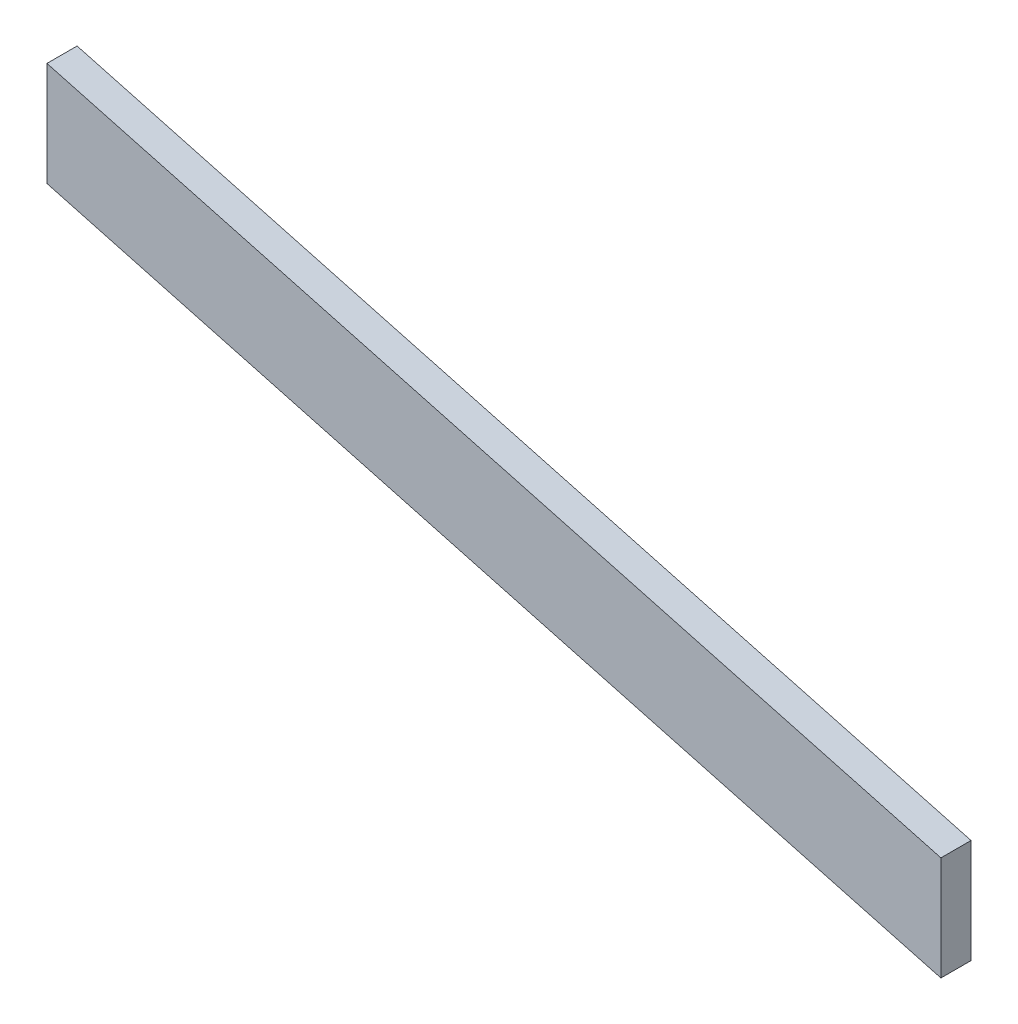
SolidWorks part; units mm, degrees
ref_plane "Front Plane" through (0, 0, 0) normal (0, 0, 1) x (1, 0, 0)
ref_plane "Top Plane" through (0, 0, 0) normal (0, 1, 0) x (1, 0, 0)
ref_plane "Right Plane" through (0, 0, 0) normal (1, 0, 0) x (0, 0, -1)
sketch "Sketch1" plane through (0, 0, 0) normal (0, 0, 1) x (1, 0, 0)
  line L0 (-108.5345, -3.9032) -> (-108.5345, 1464.0363)
  line L1 (-108.5345, -3.9032) -> (-870.5345, -3.9032)
  line L2 (-870.5345, -3.9032) -> (-870.5345, 625.8363)
  line L3 (-972.1345, 737.9573) -> (-972.1345, 834.2968)
  line L4 (-768.9345, 834.2968) -> (-768.9345, 986.6968)
  line L5 (-972.1345, 834.2968) -> (-768.9345, 834.2968)
  line L6 (-528.0858, 1843.9468) -> (-737.1845, 1843.9468)
  line L7 (-968.4148, 728.977) -> (-874.2542, 634.8165)
  line L8 (-737.1845, 1672.0154) -> (-737.1845, 1762.6932)
  line L9 (-520.195, 1875.6968) -> (-756.2345, 1875.6968)
  line L10 (-112.2542, 1473.0165) -> (-511.2148, 1871.977)
  line L11 (-737.1845, 1692.941) -> (-241.631, 1467.6894)
  line L12 (-596.8655, 1608.234) -> (-737.1845, 983.1768)
  line L13 (-763.9746, 985.3593) -> (-203.7845, 834.2968)
  line L14 (-761.4898, 1669.1128) -> (-638.6318, 1613.2683)
  line L15 (-631.4955, 1598.9249) -> (-768.9345, 986.6968)
  line L16 (-768.9345, 1680.6745) -> (-768.9345, 1862.9968)
  line L17 (-737.1845, 1780.4468) -> (-737.1845, 1843.9468)
  line L18 (-737.1845, 1692.941) -> (-737.1845, 1843.9468) construction
  line L19 (-737.1845, 1692.941) -> (-737.1845, 1762.6932) construction
  line L20 (-838.7845, -3.9032) -> (-838.7845, 834.2968)
  line L21 (-745.0674, 1675.5986) -> (-249.5139, 1450.347) construction
  line L22 (-140.2845, -3.9032) -> (-140.2845, 1456.1455)
  line L23 (-140.2845, 1456.1455) -> (-528.0858, 1843.9468)
  line L24 (-537.8111, 1581.3911) -> (-673.6845, 976.1369)
  line L25 (-768.9345, 966.9663) -> (-203.7845, 814.5663)
  line L26 (-737.1845, 1672.0154) -> (-203.7845, 1429.5608)
  line L27 (-528.0858, 1843.9468) -> (-554.3883, 1780.4468)
  line L28 (-140.2845, 1456.1455) -> (-203.7845, 1429.8429)
  line L29 (-775.2845, -3.9032) -> (-775.2845, 834.2968)
  line L30 (-773.8944, 968.3038) -> (-208.7444, 815.9038) construction
  line L31 (-203.7845, -3.9032) -> (-203.7845, 1429.8429)
  line L32 (-203.7845, 1429.8429) -> (-554.3883, 1780.4468)
  line L33 (-554.3883, 1780.4468) -> (-737.1845, 1780.4468)
  line L34 (-768.9345, 966.9663) -> (-763.9746, 985.3593)
  line L35 (-737.1845, 1762.6932) -> (-369.5099, 1595.5683)
  line L36 (-673.6845, 1733.8295) -> (-599.2171, 1699.9807) construction
  line L37 (-737.1845, 1692.941) -> (-625.4936, 1642.1724) construction
  line L38 (-538.5586, 1578.0615) -> (-673.6845, 976.1369) construction
  line L39 (-600.5166, 1591.9704) -> (-737.1845, 983.1768) construction
  line L40 (-554.3883, 1780.4468) -> (-673.6845, 1780.4468) construction
  line L41 (-203.7845, 91.3468) -> (-203.7845, 1429.8429) construction
  line L42 (-140.2845, 27.8468) -> (-140.2845, 1456.1455) construction
  line L43 (-775.2845, 91.3468) -> (-775.2845, 625.8363) construction
  line L44 (-838.7845, 27.8468) -> (-838.7845, 625.8363) construction
  line L45 (-203.7845, 91.3468) -> (-775.2845, 91.3468) construction
  line L46 (-140.2845, 27.8468) -> (-838.7845, 27.8468) construction
  line L47 (-940.3845, 745.8481) -> (-851.8036, 657.2672) construction
  line L48 (-843.7807, 739.0468) -> (-806.9023, 702.1685) construction
  line L49 (-843.7807, 739.0468) -> (-673.6845, 739.0468) construction
  line L50 (-940.3845, 802.5468) -> (-737.1845, 802.5468) construction
  line L51 (-940.3845, 745.8481) -> (-940.3845, 802.5468) construction
  line L52 (-843.7807, 739.0468) -> (-843.7807, 739.0468) construction
  line L53 (-673.6845, 1733.8295) -> (-673.6845, 1780.4468) construction
  line L54 (-756.2345, 1692.941) -> (-756.2345, 1792.2779) construction
  line L55 (-756.2345, 1792.2779) -> (-361.627, 1612.9108) construction
  line L56 (-673.6845, 739.0468) -> (-673.6845, 976.1369) construction
  line L57 (-737.1845, 802.5468) -> (-737.1845, 983.1768) construction
  line L58 (-768.9345, 986.6968) -> (-203.7845, 834.2968) construction
  line L59 (-203.7845, 834.2968) -> (-208.7444, 815.9038)
  line L60 (-768.9345, 901.198) -> (-203.7845, 748.798)
  line L61 (-846.7775, 922.1894) -> (-163.9675, 738.0608) construction
  line L62 (-768.9345, 966.9663) -> (-208.7444, 815.9038) construction
  line L64 (-808.7515, 1063.2022) -> (-125.9415, 879.0737) construction
  line L65 (-125.9415, 879.0737) -> (-163.9675, 738.0608) construction
  line L66 (-846.7775, 922.1894) -> (-808.7515, 1063.2022) construction
  arc A0 (-108.5345, 1464.0363) -> (-112.2542, 1473.0165) centre (-121.2345, 1464.0363) ccw
  arc A1 (-511.2148, 1871.977) -> (-520.195, 1875.6968) centre (-520.195, 1862.9968) ccw
  arc A2 (-768.9345, 1862.9968) -> (-756.2345, 1875.6968) centre (-756.2345, 1862.9968) cw
  arc A3 (-768.9345, 1680.6745) -> (-761.4898, 1669.1128) centre (-756.2345, 1680.6745) ccw
  arc A4 (-631.4955, 1598.9249) -> (-638.6318, 1613.2683) centre (-643.8871, 1601.7067) ccw
  arc A5 (-972.1345, 737.9573) -> (-968.4148, 728.977) centre (-959.4345, 737.9573) ccw
  arc A6 (-870.5345, 625.8363) -> (-874.2542, 634.8165) centre (-883.2345, 625.8363) ccw
  arc A7 (-737.1845, 1843.9468) -> (-737.1845, 1843.9468) centre (-737.1845, 1843.9468) cw
  arc A8 (-737.1845, 1692.941) -> (-737.1845, 1692.941) centre (-737.1845, 1692.941) ccw
  arc A12 (-140.2845, 1456.1455) -> (-140.2845, 1456.1455) centre (-140.2845, 1456.1455) ccw
  arc A13 (-528.0858, 1843.9468) -> (-528.0858, 1843.9468) centre (-528.0858, 1843.9468) ccw
  arc A14 (-600.5166, 1591.9704) -> (-625.4936, 1642.1724) centre (-643.8871, 1601.7067) ccw construction
  arc A16 (-203.7845, 1429.8429) -> (-203.7845, 1429.8429) centre (-203.7845, 1429.8429) ccw
  arc A17 (-554.3883, 1780.4468) -> (-554.3883, 1780.4468) centre (-554.3883, 1780.4468) ccw
  arc A18 (-673.6845, 1780.4468) -> (-673.6845, 1780.4468) centre (-673.6845, 1780.4468) cw
  arc A19 (-673.6845, 1733.8295) -> (-673.6845, 1733.8295) centre (-673.6845, 1733.8295) ccw
  arc A20 (-838.7845, 625.8363) -> (-851.8036, 657.2672) centre (-883.2345, 625.8363) ccw construction
  arc A21 (-775.2845, 625.8363) -> (-806.9023, 702.1685) centre (-883.2345, 625.8363) ccw construction
  arc A22 (-843.7807, 739.0468) -> (-843.7807, 739.0468) centre (-843.7807, 739.0468) ccw construction
  arc A23 (-940.3845, 745.8481) -> (-940.3845, 745.8481) centre (-940.3845, 745.8481) ccw construction
  arc A24 (-756.2345, 1692.941) -> (-745.0674, 1675.5986) centre (-737.1845, 1692.941) ccw construction
  dimension "D1" = 12.7
  dimension "D2" = 31.75
  dimension "D3" = 63.5
  dimension "D4" = 19.05
  dimension "D5" = 19.05
  dimension "D6" = 63.5
sketch "Sketch2" plane through (0, 0, 0) normal (0, 0, 1) x (1, 0, 0)
  line L0 (-768.9345, 901.198) -> (-768.9345, 966.9663)
  line L1 (-768.9345, 966.9663) -> (-203.7845, 814.5663)
  line L2 (-203.7845, 748.798) -> (-203.7845, 814.5663)
  line L3 (-768.9345, 901.198) -> (-203.7845, 748.798)
extrude "Boss-Extrude1" add sketch "Sketch2" along normal blind 19.05
